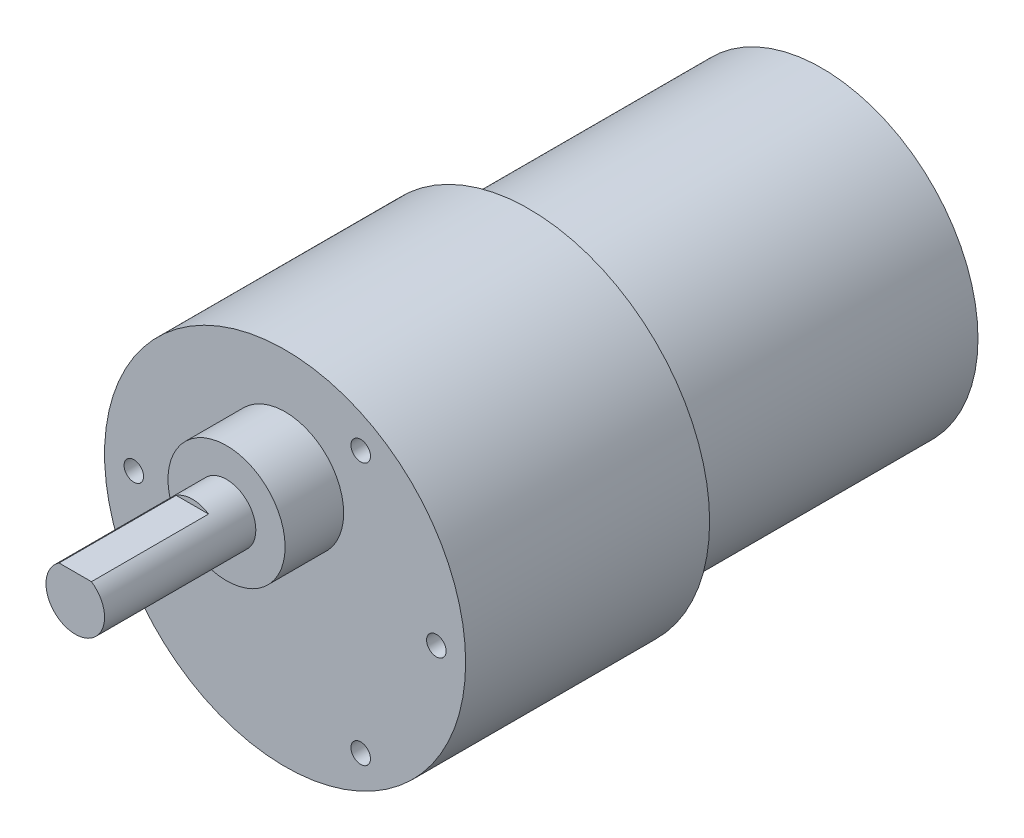
SolidWorks part; units mm, degrees
ref_plane "Plan de face" through (0, 0, 0) normal (0, 0, 1) x (1, 0, 0)
ref_plane "Plan de dessus" through (0, 0, 0) normal (0, 1, 0) x (1, 0, 0)
ref_plane "Plan de droite" through (0, 0, 0) normal (1, 0, 0) x (0, 0, -1)
sketch "Esquisse1" plane through (0, 0, 0) normal (0, 0, 1) x (1, 0, 0)
  circle A0 centre (0, 0) radius 16
  dimension "D1" = 32
extrude "Boss.-Extru.2" add sketch "Esquisse1" along normal blind 30
sketch "Esquisse2" plane through (0, 0, 30) normal (0, 0, 1) x (1, 0, 0)
  circle A0 centre (0, 0) radius 18.5
  dimension "D1" = 37
extrude "Boss.-Extru.3" add sketch "Esquisse2" along normal blind 25
sketch "Esquisse3" plane through (0, 0, 55) normal (0, 0, 1) x (1, 0, 0)
  line L0 (-27.6642, 0) -> (32.7745, 0) construction
  line L1 (0, 19.6474) -> (0, -20.4738) construction
  circle A4 centre (-15.5, 0) radius 1
  circle A5 centre (7.75, -13.4234) radius 1
  circle A6 centre (15.5, 0) radius 1
  circle A7 centre (7.75, 13.4234) radius 1
  point P10 (0, 0)
  point P17 (0, 0)
  point P20 (0, 0)
extrude "Enlèv. mat.-Extru.1" cut sketch "Esquisse3" against normal blind 3.5
sketch "Esquisse5" plane through (0, 0, 55) normal (0, 0, 1) x (1, 0, 0)
  circle A0 centre (0, 7) radius 6
  point P2 (0, 0)
  dimension "D1" = 12
  dimension "D2" = 7
extrude "Boss.-Extru.4" add sketch "Esquisse5" along normal blind 6
sketch "Esquisse6" plane through (0, 0, 61) normal (0, 0, 1) x (1, 0, 0)
  circle A0 centre (0, 7) radius 3
  point P0 (0, 7)
extrude "Boss.-Extru.5" add sketch "Esquisse6" along normal blind 15.5
sketch "Esquisse7" plane through (0, 0, 76.5) normal (0, 0, 1) x (1, 0, 0)
  line L1 (-3.6543, 10.5) -> (3.6543, 10.5)
  line L2 (-3.6543, 10.5) -> (-3.6543, 9.5)
  line L3 (-3.6543, 9.5) -> (3.6543, 9.5)
  line L4 (3.6543, 10.5) -> (3.6543, 9.5)
  line L5 (-3.6543, 10.5) -> (3.6543, 9.5) construction
  line L6 (-3.6543, 9.5) -> (3.6543, 10.5) construction
  circle A0 centre (0, 7) radius 3 construction
  circle A1 centre (0, 7) radius 3 construction
  point P0 (0, 10)
  dimension "D1" = 1
extrude "Enlèv. mat.-Extru.2" cut sketch "Esquisse7" against normal blind 12
